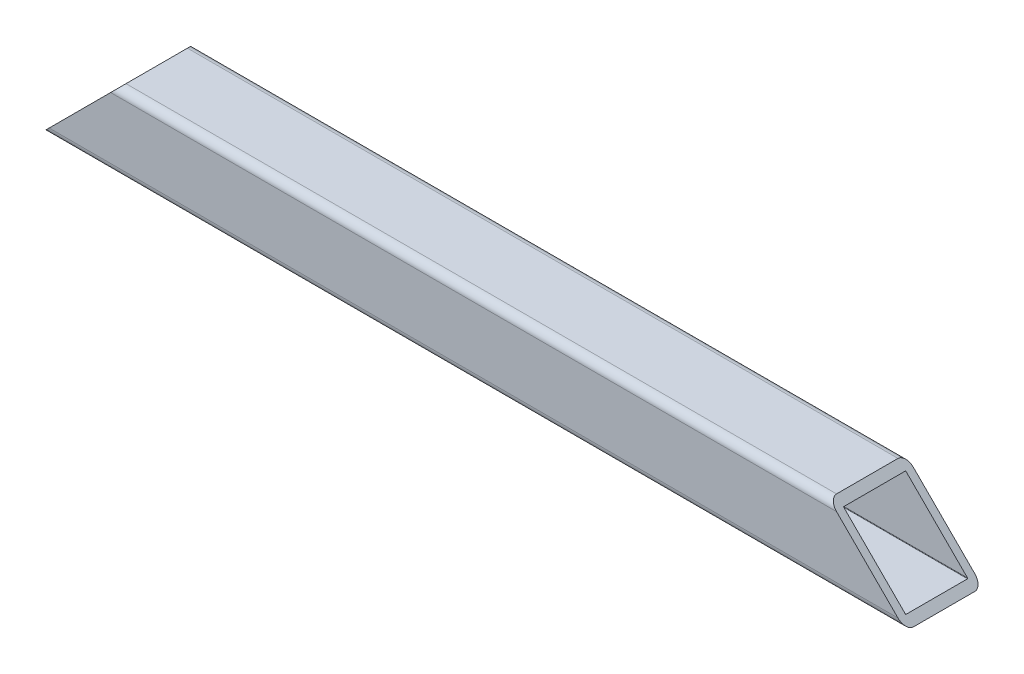
SolidWorks part; units mm, degrees
ref_plane "Front Plane" through (0, 0, 0) normal (0, 0, 1) x (1, 0, 0)
ref_plane "Top Plane" through (0, 0, 0) normal (0, 1, 0) x (1, 0, 0)
ref_plane "Right Plane" through (0, 0, 0) normal (1, 0, 0) x (0, 0, -1)
sketch "Sketch1" plane through (0, 0, 0) normal (0, 0, 1) x (1, 0, 0)
  line L0 (-68.7583, 0) -> (216.9917, 0)
  point P3 (0, 0)
  dimension "D1" = 285.75
other "Square tube - configured 2 X 2 X 0.25(1)"
ref_plane "Plane1" through (-68.7583, 0, 0) normal (1, 0, 0) x (0, 1, 0)
sketch "Sketch11" plane through (-68.7583, 0, 0) normal (1, 0, 0) x (0, 1, 0)
  line L0 (-10.16, -10.287) -> (10.16, -10.287)
  line L1 (-10.287, -10.16) -> (-10.287, 10.16)
  line L2 (10.16, 10.287) -> (-10.16, 10.287)
  line L3 (10.287, 10.16) -> (10.287, -10.16)
  line L4 (-10.16, -12.7) -> (10.16, -12.7)
  line L5 (-12.7, -10.16) -> (-12.7, 10.16)
  line L6 (10.16, 12.7) -> (-10.16, 12.7)
  line L7 (12.7, 10.16) -> (12.7, -10.16)
  line L8 (0, 0) -> (10.287, 0) construction
  line L9 (0, 0) -> (0, 10.287) construction
  arc A0 (12.7, 10.16) -> (10.16, 12.7) centre (10.16, 10.16) ccw
  arc A1 (10.16, -12.7) -> (12.7, -10.16) centre (10.16, -10.16) ccw
  arc A2 (-12.7, -10.16) -> (-10.16, -12.7) centre (-10.16, -10.16) ccw
  arc A3 (-10.16, 12.7) -> (-12.7, 10.16) centre (-10.16, 10.16) ccw
  arc A4 (-10.16, 10.287) -> (-10.287, 10.16) centre (-10.16, 10.16) ccw
  arc A5 (10.287, 10.16) -> (10.16, 10.287) centre (10.16, 10.16) ccw
  arc A6 (10.16, -10.287) -> (10.287, -10.16) centre (10.16, -10.16) ccw
  arc A7 (-10.287, -10.16) -> (-10.16, -10.287) centre (-10.16, -10.16) ccw
  point P3 (0, 12.7)
  point P4 (12.7, 0)
  point P5 (0, -12.7)
  point P6 (-12.7, 0)
  point P7 (-12.7, 12.7)
  point P8 (-12.7, -12.7)
  point P33 (0, 0)
  point P35 (12.7, -12.7)
  point P36 (12.7, 12.7)
  point P37 (0, 0)
  dimension "D1" = 2.54
  dimension "Thickness" = 2.413
  dimension "V_leg" = 25.4
sketch "Sketch12" plane through (0, 0, 0) normal (0, 0, 1) x (1, 0, 0)
  line L0 (-68.7583, -12.7) -> (-43.3583, 12.7)
  line L1 (216.9917, 12.7) -> (-68.7583, 12.7) construction
  line L2 (-43.3583, 12.7) -> (-68.7583, 12.7)
  line L3 (-68.7583, -12.7) -> (-68.7583, 12.7)
  line L4 (216.9917, -12.7) -> (191.5917, 12.7)
  line L5 (191.5917, 12.7) -> (216.9917, 12.7)
  line L6 (216.9917, 12.7) -> (216.9917, -12.7)
  line L7 (216.9917, -12.7) -> (-68.7583, -12.7) construction
  dimension "D1" = 45
  dimension "D2" = 45
extrude "Cut-Extrude1" cut sketch "Sketch12" against normal through all both and the other way through all
